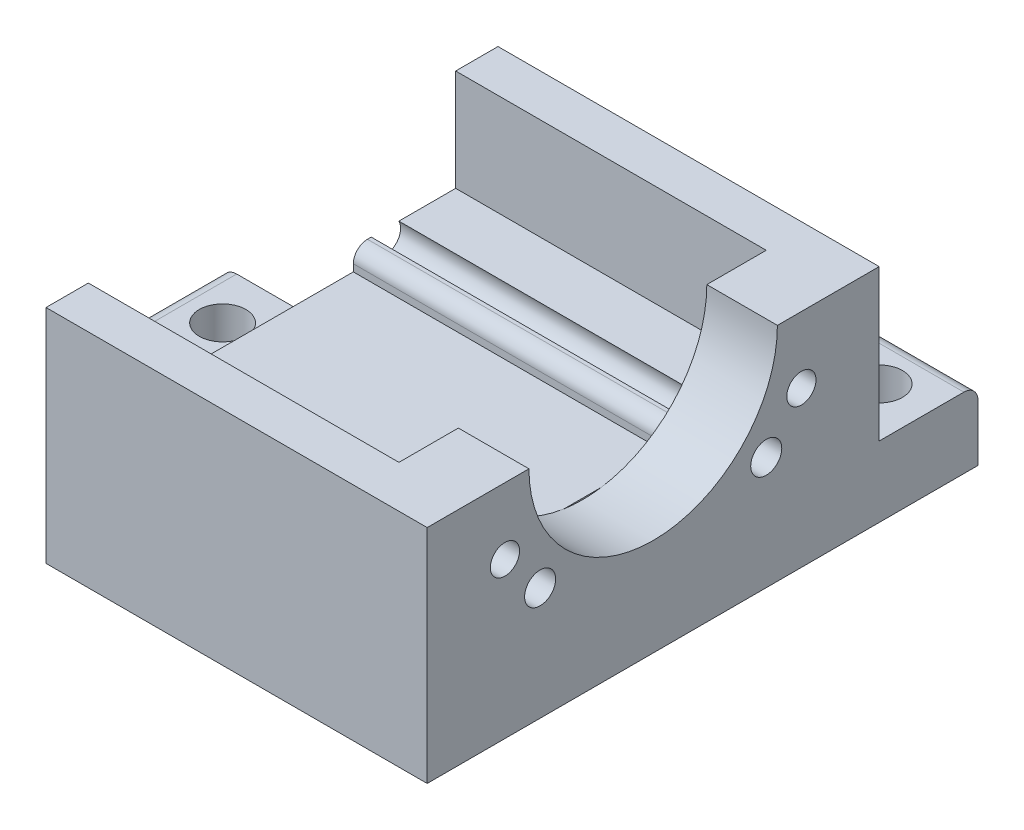
SolidWorks part; units mm, degrees
ref_plane "Front" through (0, 0, 0) normal (0, 0, 1) x (1, 0, 0)
ref_plane "Top" through (0, 0, 0) normal (0, 1, 0) x (1, 0, 0)
ref_plane "Right" through (0, 0, 0) normal (1, 0, 0) x (0, 0, -1)
sketch "Sketch1" plane through (0, 0, 0) normal (1, 0, 0) x (0, 0, -1)
  line L0 (-13.0089, 0) -> (13.0089, 0)
  line L1 (13.0089, 0) -> (13.0089, 8.5)
  line L2 (13.0089, 8.5) -> (5.7589, 8.5)
  line L3 (5.7589, 8.5) -> (5.7589, 7)
  line L4 (5.7589, 7) -> (-5.7589, 7)
  line L5 (-5.7589, 7) -> (-5.7589, 8.5)
  line L6 (-5.7589, 8.5) -> (-13.0089, 8.5)
  line L7 (-13.0089, 8.5) -> (-13.0089, 0)
  dimension "D1" = 8.5
  dimension "D2" = 7.25
  dimension "D3" = 26.0178
  dimension "D4" = 1.5
extrude "Boss-Extrude1" add sketch "Sketch1" along normal mid plane 22
sketch "Sketch3" plane through (0, 0, 0) normal (0, -1, 0) x (1, 0, 0)
  line L1 (-11, -13.0089) -> (11, -13.0089)
  line L2 (-11, -13.0089) -> (-11, -16.0089)
  line L3 (-11, -16.0089) -> (11, -16.0089)
  line L4 (11, -13.0089) -> (11, -16.0089)
  line L5 (-11, 13.0089) -> (11, 13.0089)
  line L6 (-11, 13.0089) -> (-11, 16.0089)
  line L7 (-11, 16.0089) -> (11, 16.0089)
  line L8 (11, 13.0089) -> (11, 16.0089)
  dimension "D1" = 3
  dimension "D2" = 22
  dimension "D3" = 3
  dimension "D4" = 22
extrude "Boss-Extrude2" add sketch "Sketch3" against normal blind 15.7
sketch "Sketch4" plane through (11, 0, 0) normal (1, 0, 0) x (0, 0, -1)
  line L0 (0, 0) -> (0, 15.7) construction
  line L1 (-16.0089, 0) -> (16.0089, 0) construction
  line L2 (-8.8, 15.7) -> (-16.0089, 15.7)
  line L3 (-16.0089, 15.7) -> (-16.0089, 0) construction
  line L4 (-16.0089, 15.7) -> (-16.0089, 0)
  line L5 (-16.0089, 0) -> (16.0089, 0)
  line L6 (16.0089, 0) -> (16.0089, 15.7)
  line L7 (16.0089, 15.7) -> (16.0089, 0) construction
  line L8 (16.0089, 15.7) -> (8.8, 15.7)
  arc A0 (-8.8, 15.7) -> (8.8, 15.7) centre (0, 15.7) ccw
  dimension "D1" = 8.8
  dimension "D2" = 15.7
extrude "Boss-Extrude3" add sketch "Sketch4" along normal blind 5
sketch "Sketch5" plane through (16, 0, 0) normal (1, 0, 0) x (0, 0, -1)
  line L0 (-16.0089, 11) -> (-10.5, 11) construction
  line L1 (-16.0089, 15.7) -> (-16.0089, 0) construction
  line L2 (-10.5, 11) -> (-10.5, 0) construction
  line L3 (-16.0089, 0) -> (16.0089, 0) construction
  line L4 (0, 0) -> (0, 15.7) construction
  line L5 (-16.0089, 8) -> (-8.0089, 8) construction
  line L6 (-8.0089, 8) -> (-8.0089, 0) construction
  circle A0 centre (-10.5, 11) radius 1.035
  circle A1 centre (10.5, 11) radius 1.035
  circle A2 centre (-8.0089, 8) radius 1.1
  circle A3 centre (8.0089, 8) radius 1.1
  dimension "D3" = 2.07
  dimension "D4" = 2.2
  dimension "D1" = 5.5089
  dimension "D2" = 11
  dimension "D5" = 8
  dimension "D6" = 8
extrude "Cut-Extrude1" cut sketch "Sketch5" against normal through all
sketch "Sketch6" plane through (0, 0, 0) normal (0, -1, 0) x (1, 0, 0)
  line L5 (0, 0) -> (-11, 0) construction
  line L6 (16, -23.0089) -> (9, -23.0089)
  line L8 (16, -16.0089) -> (16, -23.0089)
  line L11 (9, -23.0089) -> (9, -16.0089)
  line L12 (9, -16.0089) -> (16, -16.0089)
  line L13 (-11, -16.0089) -> (16, -16.0089) construction
  line L14 (-11, 16.0089) -> (-11, -16.0089) construction
  line L16 (-11, 3.5) -> (-18, 3.5)
  line L17 (-11, 3.5) -> (-11, -3.5)
  line L18 (-11, -3.5) -> (-18, -3.5)
  line L19 (-18, 3.5) -> (-18, -3.5)
  dimension "D1" = 7
  dimension "D2" = 7
  dimension "D3" = 7
  dimension "D4" = 7
extrude "Boss-Extrude4" add sketch "Sketch6" against normal blind 5
sketch "Sketch7" plane through (0, 5, 0) normal (0, 1, 0) x (1, 0, 0)
  line L0 (-11, 0) -> (-18, 0) construction
  line L1 (-11, 3.5) -> (-11, -3.5) construction
  line L2 (-18, -3.5) -> (-18, 3.5) construction
  line L3 (-14.5, 3.5) -> (-14.5, -3.5) construction
  line L4 (-18, 3.5) -> (-11, 3.5) construction
  line L5 (-11, -3.5) -> (-18, -3.5) construction
  line L6 (12.5, 23.0089) -> (12.5, 16.0089) construction
  line L7 (9, 23.0089) -> (16, 23.0089) construction
  line L8 (16, 16.0089) -> (9, 16.0089) construction
  line L9 (9, 19.5089) -> (16, 19.5089) construction
  line L10 (9, 16.0089) -> (9, 23.0089) construction
  line L11 (16, 23.0089) -> (16, 16.0089) construction
  circle A0 centre (-14.5, 0) radius 1.65
  circle A1 centre (12.5, 19.5089) radius 1.65
  dimension "D1" = 3.3
extrude "Cut-Extrude2" cut sketch "Sketch7" against normal through all
fillet "Fillet1" radius 1 4 edges at (12.5, 5, -23.0089) (-18, 5, 0) (0, 8.5, 5.7589) (0, 8.5, -5.7589)
